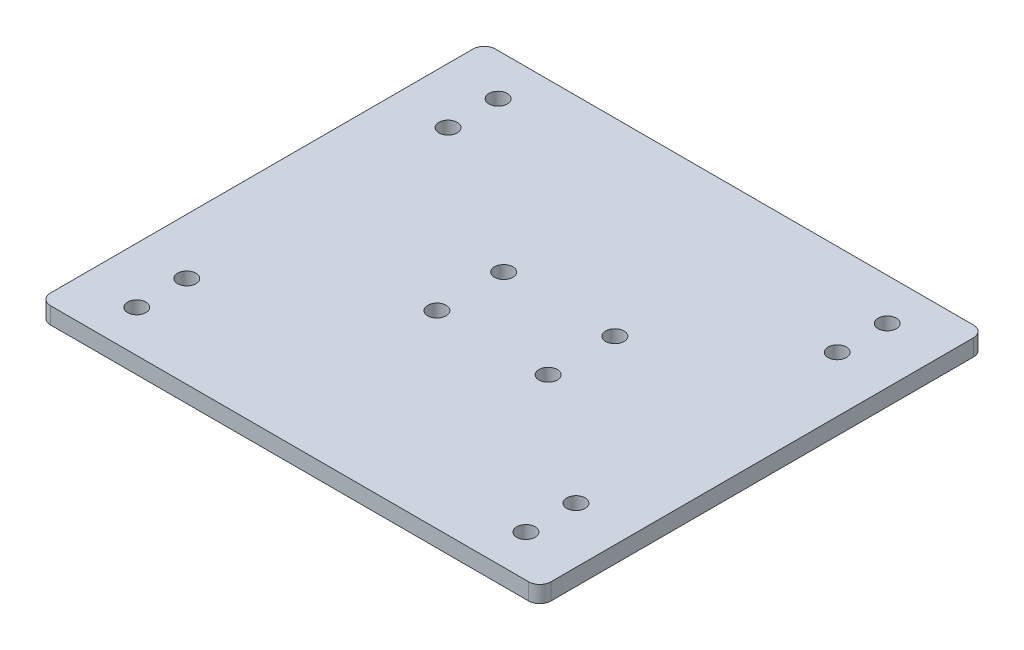
SolidWorks part; units mm, degrees
ref_plane "前视基准面" through (0, 0, 0) normal (0, 0, 1) x (1, 0, 0)
ref_plane "上视基准面" through (0, 0, 0) normal (0, 1, 0) x (1, 0, 0)
ref_plane "右视基准面" through (0, 0, 0) normal (1, 0, 0) x (0, 0, -1)
sketch "草图1" plane through (0, 0, 0) normal (0, 1, 0) x (1, 0, 0)
  line L1 (-45, -40) -> (45, -40)
  line L2 (-45, -40) -> (-45, 40)
  line L3 (-45, 40) -> (45, 40)
  line L4 (45, -40) -> (45, 40)
  line L5 (-45, -40) -> (45, 40) construction
  line L6 (-45, 40) -> (45, -40) construction
  point P0 (0, 0)
  dimension "D1" = 90
  dimension "D2" = 80
extrude "凸台-拉伸1" add sketch "草图1" along normal mid plane 3
sketch "草图2" plane through (0, 1.5, 0) normal (0, 1, 0) x (1, 0, 0)
  line L0 (-59.4101, 0) -> (57.7541, 0) construction
  line L2 (-7.5, -6) -> (12.5, -6) construction
  line L3 (-7.5, -6) -> (-7.5, 6) construction
  line L4 (-7.5, 6) -> (12.5, 6) construction
  line L5 (12.5, -6) -> (12.5, 6) construction
  line L6 (-7.5, -6) -> (12.5, 6) construction
  line L7 (-7.5, 6) -> (12.5, -6) construction
  circle A0 centre (12.5, 6) radius 1.65
  circle A1 centre (-7.5, 6) radius 1.65
  circle A2 centre (-7.5, -6) radius 1.65
  circle A3 centre (12.5, -6) radius 1.65
  point P3 (2.5, 0)
  dimension "D4" = 3.3
  dimension "D5" = 3.3
  dimension "D6" = 3.3
  dimension "D7" = 3.3
  dimension "D1" = 20
  dimension "D2" = 12
  dimension "D3" = 2.5
extrude "切除-拉伸1" cut sketch "草图2" against normal blind 3
fillet "圆角1" radius 2 4 edges at (-45, 0, -40) (45, 0, -40) (45, 0, 40) (-45, 0, 40)
sketch "草图3" plane through (0, 1.5, 0) normal (0, 1, 0) x (1, 0, 0)
  line L0 (35, 49.9915) -> (35, -54.5869) construction
  line L1 (45, -38) -> (45, 38) construction
  line L2 (-43, -40) -> (43, -40) construction
  line L4 (43, 40) -> (-43, 40) construction
  circle A0 centre (35, 32.5) radius 1.65
  circle A1 centre (35, 23.5) radius 1.65
  circle A2 centre (35, -23.5) radius 1.65
  circle A3 centre (35, -32.5) radius 1.65
  dimension "D4" = 7.5
  dimension "D5" = 9
  dimension "D6" = 3.3
  dimension "D7" = 3.3
  dimension "D8" = 3.3
  dimension "D9" = 3.3
  dimension "D1" = 10
  dimension "D2" = 7.5
  dimension "D3" = 9
extrude "切除-拉伸2" cut sketch "草图3" against normal blind 3
mirror "镜向1" about plane through (0, 0, 0) normal (1, 0, 0) of "切除-拉伸2" second plane through (0, 0, 0) second plane normal (0, 0, 1)
